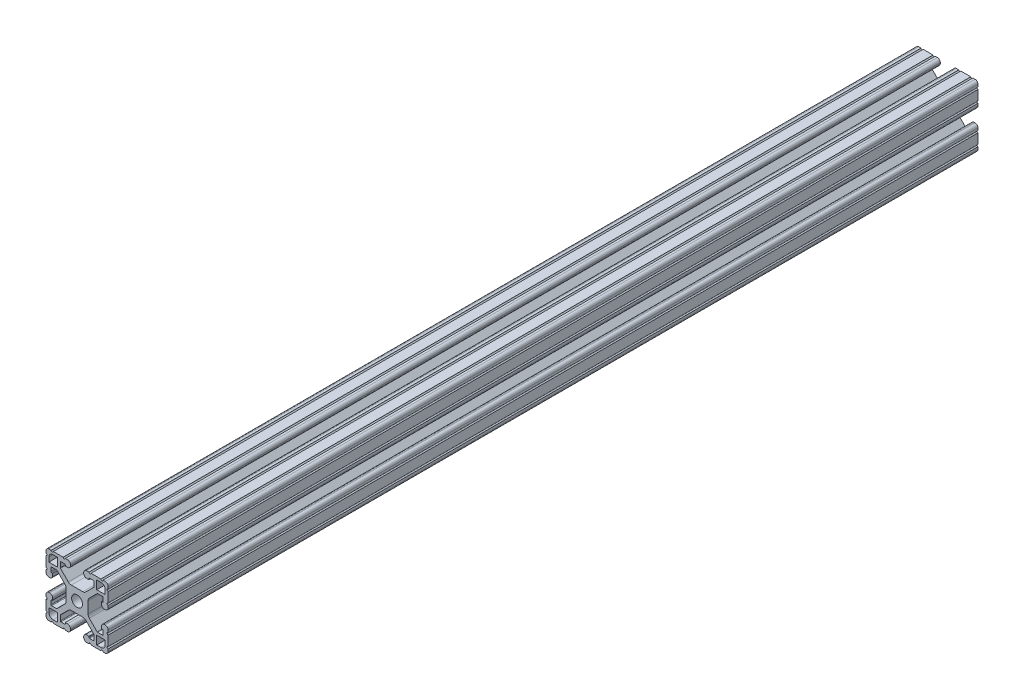
SolidWorks part; units mm, degrees
ref_plane "Front Plane" through (0, 0, 0) normal (0, 0, 1) x (1, 0, 0)
ref_plane "Top Plane" through (0, 0, 0) normal (0, 1, 0) x (1, 0, 0)
ref_plane "Right Plane" through (0, 0, 0) normal (1, 0, 0) x (0, 0, -1)
sketch "Sketch1" plane through (0, 0, 0) normal (0, 0, 1) x (1, 0, 0)
  line L0 (0, -19.05) -> (0, 19.05) construction
  line L1 (19.05, 0) -> (-19.05, 0) construction
  line L2 (4.064, 19.05) -> (-4.064, 19.05) construction
  line L3 (0, -6.7564) -> (0, 6.7564) construction
  line L4 (-4.064, 19.05) -> (-4.064, 14.986) construction
  line L5 (19.05, -10.287) -> (19.05, 10.287) construction
  line L6 (0, -3.3274) -> (0, 3.3274) construction
  line L7 (0, 0) -> (-19.05, 19.05) construction
  line L8 (-8.4474, 10.6026) -> (-10.6026, 8.4474) construction
  point P4 (0, 0)
  point P8 (0, 0)
  point P11 (0, 19.05)
  point P14 (0, 0)
  point P18 (19.05, 0)
  point P21 (0, 0)
  point P24 (-9.525, 9.525)
  point P26 (-9.525, 9.525)
  dimension "T-Slot Width" = 8.128
  dimension "Thickness" = 4.064
  dimension "Opening Width" = 20.574
  dimension "Slot Depth" = 12.2936
  dimension "Center Hole Diameter" = 6.6548
  dimension "Rail Height" = 38.1
  dimension "Rail Width" = 38.1
  dimension "D1" = 45
  dimension "Wall" = 3.048
sketch "Sketch2" plane through (0, 0, 0) normal (1, 0, 0) x (0, 0, -1)
  line L0 (-266.7, 0) -> (266.7, 0) construction
  line L1 (-190.5, -19.05) -> (-190.5, 19.05) construction
  line L2 (190.5, -19.05) -> (190.5, 19.05) construction
  line L3 (0, -19.05) -> (0, 19.05) construction
  point P4 (0, 0)
  point P7 (-190.5, 0)
  point P10 (190.5, 0)
  dimension "Length" = 533.4
  dimension "D1" = 76.2
  dimension "D2" = 76.2
sketch "Sketch3" plane through (0, 0, 0) normal (0, 0, 1) x (1, 0, 0)
  line L1 (19.05, -19.05) -> (-19.05, -19.05)
  line L2 (19.05, -19.05) -> (19.05, 19.05)
  line L3 (19.05, 19.05) -> (-19.05, 19.05)
  line L4 (-19.05, -19.05) -> (-19.05, 19.05)
  line L5 (19.05, -19.05) -> (-19.05, 19.05) construction
  line L6 (19.05, 19.05) -> (-19.05, -19.05) construction
  point P0 (0, 0)
extrude "Boss-Extrude1" add sketch "Sketch3" along normal up to vertex (266.7 mm away) and the other way up to vertex (266.7 mm away) up to point (0, 0, 266.7) other way up to point (0, 0, -266.7)
sketch "Sketch4" plane through (0, 0, 266.7) normal (0, 0, 1) x (1, 0, 0)
  line L4 (4.064, 14.986) -> (4.064, 19.05)
  line L5 (7.239, 14.986) -> (4.064, 14.986)
  line L6 (19.05, 0) -> (-19.05, 0) construction
  line L7 (4.6011, 6.7564) -> (-4.6011, 6.7564)
  line L8 (-4.6011, 6.7564) -> (-10.287, 12.4423)
  line L37 (-19.05, 19.05) -> (-19.05, -19.05) construction
  line L38 (-19.05, -19.05) -> (19.05, -19.05) construction
  line L39 (-10.287, 12.4423) -> (-10.287, 16.002)
  line L40 (-10.287, 16.002) -> (-7.239, 16.002)
  line L41 (-7.239, 16.002) -> (-7.239, 14.986)
  line L42 (-7.239, 14.986) -> (-4.064, 14.986)
  line L43 (-4.064, 14.986) -> (-4.064, 19.05)
  line L44 (-4.064, 19.05) -> (4.064, 19.05)
  line L45 (0, 19.05) -> (0, 0) construction
  line L46 (-19.05, 19.05) -> (0, 0) construction
  line L47 (7.239, 16.002) -> (7.239, 14.986)
  line L48 (10.287, 16.002) -> (7.239, 16.002)
  line L49 (10.287, 12.4423) -> (10.287, 16.002)
  line L50 (4.6011, 6.7564) -> (10.287, 12.4423)
  line L51 (-19.05, 0) -> (19.05, 0) construction
  line L52 (4.6011, -6.7564) -> (10.287, -12.4423)
  line L53 (10.287, -12.4423) -> (10.287, -16.002)
  line L54 (10.287, -16.002) -> (7.239, -16.002)
  line L55 (7.239, -16.002) -> (7.239, -14.986)
  line L56 (-4.064, -19.05) -> (4.064, -19.05)
  line L57 (-4.064, -14.986) -> (-4.064, -19.05)
  line L58 (-7.239, -14.986) -> (-4.064, -14.986)
  line L59 (-7.239, -16.002) -> (-7.239, -14.986)
  line L60 (-10.287, -16.002) -> (-7.239, -16.002)
  line L61 (-10.287, -12.4423) -> (-10.287, -16.002)
  line L62 (-4.6011, -6.7564) -> (-10.287, -12.4423)
  line L63 (4.6011, -6.7564) -> (-4.6011, -6.7564)
  line L64 (7.239, -14.986) -> (4.064, -14.986)
  line L65 (4.064, -14.986) -> (4.064, -19.05)
  line L66 (-6.7564, -4.6011) -> (-12.4423, -10.287)
  line L67 (-12.4423, -10.287) -> (-16.002, -10.287)
  line L68 (-16.002, -10.287) -> (-16.002, -7.239)
  line L69 (-16.002, -7.239) -> (-14.986, -7.239)
  line L70 (-19.05, 4.064) -> (-19.05, -4.064)
  line L71 (-14.986, 4.064) -> (-19.05, 4.064)
  line L72 (-14.986, 7.239) -> (-14.986, 4.064)
  line L73 (-16.002, 7.239) -> (-14.986, 7.239)
  line L74 (-16.002, 10.287) -> (-16.002, 7.239)
  line L75 (-12.4423, 10.287) -> (-16.002, 10.287)
  line L76 (-6.7564, 4.6011) -> (-12.4423, 10.287)
  line L77 (-6.7564, -4.6011) -> (-6.7564, 4.6011)
  line L78 (-14.986, -7.239) -> (-14.986, -4.064)
  line L79 (-14.986, -4.064) -> (-19.05, -4.064)
  line L80 (14.986, -4.064) -> (19.05, -4.064)
  line L81 (14.986, -7.239) -> (14.986, -4.064)
  line L82 (6.7564, -4.6011) -> (6.7564, 4.6011)
  line L83 (6.7564, 4.6011) -> (12.4423, 10.287)
  line L84 (12.4423, 10.287) -> (16.002, 10.287)
  line L85 (16.002, 10.287) -> (16.002, 7.239)
  line L86 (16.002, 7.239) -> (14.986, 7.239)
  line L87 (14.986, 7.239) -> (14.986, 4.064)
  line L88 (14.986, 4.064) -> (19.05, 4.064)
  line L89 (19.05, 4.064) -> (19.05, -4.064)
  line L90 (16.002, -7.239) -> (14.986, -7.239)
  line L91 (16.002, -10.287) -> (16.002, -7.239)
  line L92 (12.4423, -10.287) -> (16.002, -10.287)
  line L93 (6.7564, -4.6011) -> (12.4423, -10.287)
  line L94 (19.05, -19.05) -> (19.05, 19.05) construction
  line L95 (12.065, 17.272) -> (17.272, 17.272)
  line L96 (12.065, 17.272) -> (12.065, 12.065)
  line L97 (12.065, 12.065) -> (17.272, 12.065)
  line L98 (17.272, 17.272) -> (17.272, 12.065)
  line L99 (19.05, 19.05) -> (-19.05, 19.05) construction
  line L100 (17.272, -17.272) -> (17.272, -12.065)
  line L101 (12.065, -17.272) -> (17.272, -17.272)
  line L102 (12.065, -17.272) -> (12.065, -12.065)
  line L103 (12.065, -12.065) -> (17.272, -12.065)
  line L104 (-17.272, 17.272) -> (-17.272, 12.065)
  line L105 (-12.065, 12.065) -> (-17.272, 12.065)
  line L106 (-12.065, 17.272) -> (-12.065, 12.065)
  line L107 (-12.065, 17.272) -> (-17.272, 17.272)
  line L108 (-12.065, -12.065) -> (-17.272, -12.065)
  line L109 (-12.065, -17.272) -> (-12.065, -12.065)
  line L110 (-12.065, -17.272) -> (-17.272, -17.272)
  line L111 (-17.272, -17.272) -> (-17.272, -12.065)
  circle A5 centre (0, 0) radius 3.3274
  point P21 (0, 6.7564)
  point P23 (0, -6.7564)
  point P38 (-6.7564, 0)
  point P53 (6.7564, 0)
  dimension "D1" = 20.574
  dimension "D3" = 3.048
  dimension "D4" = 3.048
  dimension "D5" = 1.778
  dimension "D6" = 1.778
  dimension "D7" = 1.778
extrude "Cut-Extrude1" cut sketch "Sketch4" against normal through all
sketch "Sketch5" plane through (0, 0, 266.7) normal (0, 0, 1) x (1, 0, 0)
  line L4 (-4.064, 19.05) -> (-19.05, 19.05) construction
  line L26 (-19.05, 19.05) -> (-19.05, 4.064) construction
  line L27 (-15.875, 19.05) -> (-14.605, 19.05)
  line L28 (-8.509, 19.05) -> (-7.239, 19.05)
  line L29 (-19.05, 15.875) -> (-19.05, 14.605)
  line L30 (-19.05, 8.509) -> (-19.05, 7.239)
  line L31 (8.509, 19.05) -> (7.239, 19.05)
  line L32 (15.875, 19.05) -> (14.605, 19.05)
  line L33 (19.05, 15.875) -> (19.05, 14.605)
  line L34 (19.05, 8.509) -> (19.05, 7.239)
  line L35 (19.05, -8.509) -> (19.05, -7.239)
  line L36 (19.05, -15.875) -> (19.05, -14.605)
  line L37 (15.875, -19.05) -> (14.605, -19.05)
  line L38 (8.509, -19.05) -> (7.239, -19.05)
  line L39 (-8.509, -19.05) -> (-7.239, -19.05)
  line L40 (-15.875, -19.05) -> (-14.605, -19.05)
  line L41 (-19.05, -15.875) -> (-19.05, -14.605)
  line L42 (-19.05, -8.509) -> (-19.05, -7.239)
  line L43 (19.05, 19.05) -> (4.064, 19.05) construction
  line L44 (19.05, 4.064) -> (19.05, 19.05) construction
  line L48 (-14.986, 4.064) -> (-19.05, 4.064) construction
  line L49 (-4.064, 14.986) -> (-4.064, 19.05) construction
  arc A8 (-15.875, 19.05) -> (-14.605, 19.05) centre (-15.24, 19.05) ccw
  arc A9 (-8.509, 19.05) -> (-7.239, 19.05) centre (-7.874, 19.05) ccw
  arc A10 (-19.05, 14.605) -> (-19.05, 15.875) centre (-19.05, 15.24) ccw
  arc A11 (-19.05, 7.239) -> (-19.05, 8.509) centre (-19.05, 7.874) ccw
  arc A12 (7.239, 19.05) -> (8.509, 19.05) centre (7.874, 19.05) ccw
  arc A13 (14.605, 19.05) -> (15.875, 19.05) centre (15.24, 19.05) ccw
  arc A14 (19.05, 15.875) -> (19.05, 14.605) centre (19.05, 15.24) ccw
  arc A15 (19.05, 8.509) -> (19.05, 7.239) centre (19.05, 7.874) ccw
  arc A16 (19.05, -7.239) -> (19.05, -8.509) centre (19.05, -7.874) ccw
  arc A17 (19.05, -14.605) -> (19.05, -15.875) centre (19.05, -15.24) ccw
  arc A18 (15.875, -19.05) -> (14.605, -19.05) centre (15.24, -19.05) ccw
  arc A19 (8.509, -19.05) -> (7.239, -19.05) centre (7.874, -19.05) ccw
  arc A20 (-7.239, -19.05) -> (-8.509, -19.05) centre (-7.874, -19.05) ccw
  arc A21 (-14.605, -19.05) -> (-15.875, -19.05) centre (-15.24, -19.05) ccw
  arc A22 (-19.05, -15.875) -> (-19.05, -14.605) centre (-19.05, -15.24) ccw
  arc A23 (-19.05, -8.509) -> (-19.05, -7.239) centre (-19.05, -7.874) ccw
  dimension "D2" = 0.635
  dimension "D4" = 3.81
  dimension "D5" = 3.81
  dimension "D1" = 3.81
  dimension "D3" = 3.81
  dimension "D7" = 4
extrude "Cut-Extrude2" cut sketch "Sketch5" against normal through all
fillet "Fillet1" radius 2.54 12 edges at (-6.7564, 4.6011, 0) (-6.7564, -4.6011, 0) (4.6011, -6.7564, 0) (-4.6011, -6.7564, 0) (6.7564, -4.6011, 0) (6.7564, 4.6011, 0) (4.6011, 6.7564, 0) (-4.6011, 6.7564, 0) (-17.272, 17.272, 0) (17.272, 17.272, 0) (17.272, -17.272, 0) (-17.272, -17.272, 0)
fillet "Fillet2" radius 1.778 20 edges at (19.05, -19.05, 0) (19.05, 19.05, 0) (-19.05, -19.05, 0) (-19.05, 19.05, 0) (-14.986, 4.064, 0) (-19.05, 4.064, 0) (-19.05, -4.064, 0) (-14.986, -4.064, 0) (-4.064, -19.05, 0) (-4.064, -14.986, 0) (4.064, -14.986, 0) (4.064, -19.05, 0) (19.05, -4.064, 0) (14.986, -4.064, 0) (19.05, 4.064, 0) (14.986, 4.064, 0) (4.064, 14.986, 0) (4.064, 19.05, 0) (-4.064, 19.05, 0) (-4.064, 14.986, 0)
fillet "Fillet3" radius 0.3969 24 edges at (-14.986, -7.239, 0) (-16.002, -10.287, 0) (-12.4423, -10.287, 0) (-12.4423, 10.287, 0) (-16.002, 7.239, 0) (-16.002, 10.287, 0) (-10.287, 12.4423, 0) (-7.239, 16.002, 0) (-10.287, 16.002, 0) (10.287, 16.002, 0) (7.239, 16.002, 0) (10.287, 12.4423, 0) (16.002, 10.287, 0) (12.4423, 10.287, 0) (16.002, 7.239, 0) (16.002, -7.239, 0) (16.002, -10.287, 0) (12.4423, -10.287, 0) (10.287, -12.4423, 0) (10.287, -16.002, 0) (7.239, -16.002, 0) (-7.239, -16.002, 0) (-10.287, -12.4423, 0) (-10.287, -16.002, 0)
equation "\"D4@Sketch5\"=\"D3@Sketch5\""
equation "\"D5@Sketch5\"=\"D4@Sketch5\""
equation "\"D1@Sketch4\"=\"Opening Width@Sketch1\""
equation "\"D2@Sketch2\"=\"D1@Sketch2\""
